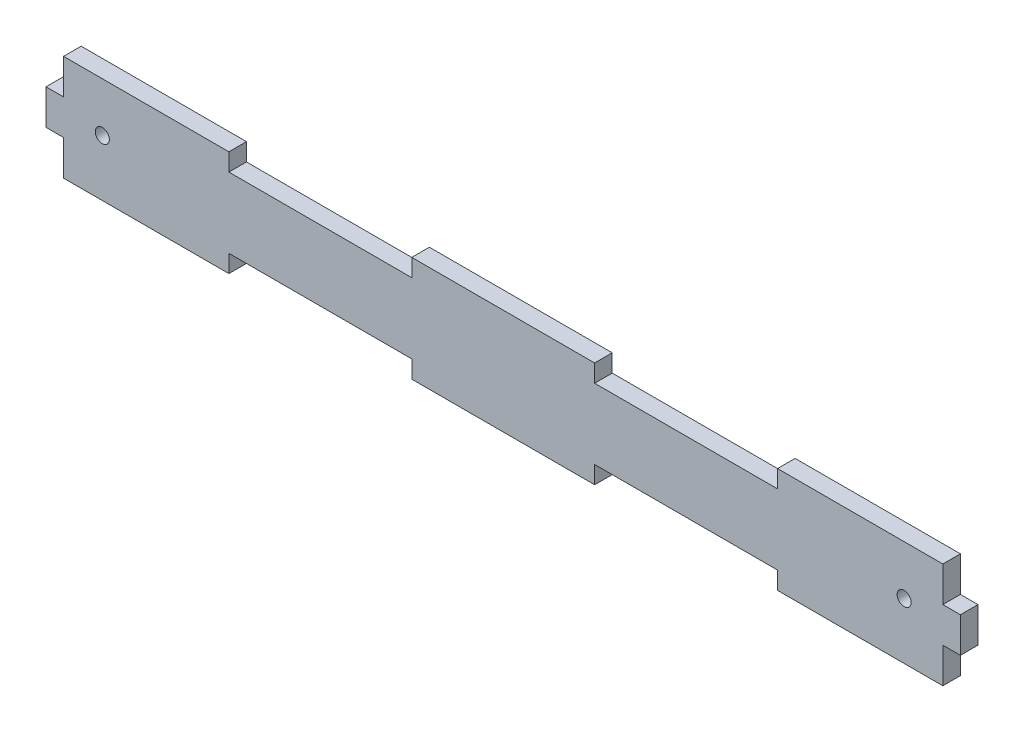
SolidWorks part; units mm, degrees
ref_plane "Alzado" through (0, 0, 0) normal (0, 0, 1) x (1, 0, 0)
ref_plane "Planta" through (0, 0, 0) normal (0, 1, 0) x (1, 0, 0)
ref_plane "Vista lateral" through (0, 0, 0) normal (1, 0, 0) x (0, 0, -1)
sketch "Croquis1" plane through (0, 0, 0) normal (0, 0, 1) x (1, 0, 0)
  line L0 (0, 20) -> (5, 20)
  line L1 (5, 0) -> (52, 0)
  line L2 (0, 10) -> (0, 20)
  line L3 (5, 30) -> (52, 30)
  line L4 (260, 10) -> (260, 20)
  line L5 (5, 20) -> (5, 10) construction
  line L6 (5, 10) -> (0, 10)
  line L7 (130, 30) -> (130, 31.9566) construction
  line L8 (0, 15) -> (30.953, 15) construction
  line L9 (5, 20) -> (5, 30)
  line L10 (5, 10) -> (5, 0)
  line L11 (0, 0) -> (5, 0) construction
  line L12 (0, 0) -> (0, 10) construction
  line L13 (255, 10) -> (255, 0)
  line L14 (255, 10) -> (260, 10)
  line L15 (260, 20) -> (255, 20)
  line L16 (255, 20) -> (255, 30)
  line L17 (52, 0) -> (52, 5)
  line L18 (52, 5) -> (104, 5)
  line L19 (104, 5) -> (104, 0)
  line L20 (156, 5) -> (156, 0)
  line L21 (208, 5) -> (156, 5)
  line L22 (208, 0) -> (208, 5)
  line L23 (208, 30) -> (208, 25)
  line L24 (208, 25) -> (156, 25)
  line L25 (156, 25) -> (156, 30)
  line L26 (104, 25) -> (104, 30)
  line L27 (52, 25) -> (104, 25)
  line L28 (52, 30) -> (52, 25)
  line L29 (104, 30) -> (156, 30)
  line L30 (208, 30) -> (255, 30)
  line L31 (104, 0) -> (156, 0)
  line L32 (208, 0) -> (255, 0)
  circle A0 centre (16, 16) radius 2
  circle A1 centre (244, 16) radius 2
  dimension "D3" = 4
  dimension "D1" = 260
  dimension "D2" = 30
  dimension "D4" = 10
  dimension "D5" = 5
  dimension "D6" = 52
  dimension "D7" = 52
  dimension "D8" = 5
  dimension "D9" = 16
  dimension "D10" = 16
extrude "Saliente-Extruir1" add sketch "Croquis1" along normal blind 5
